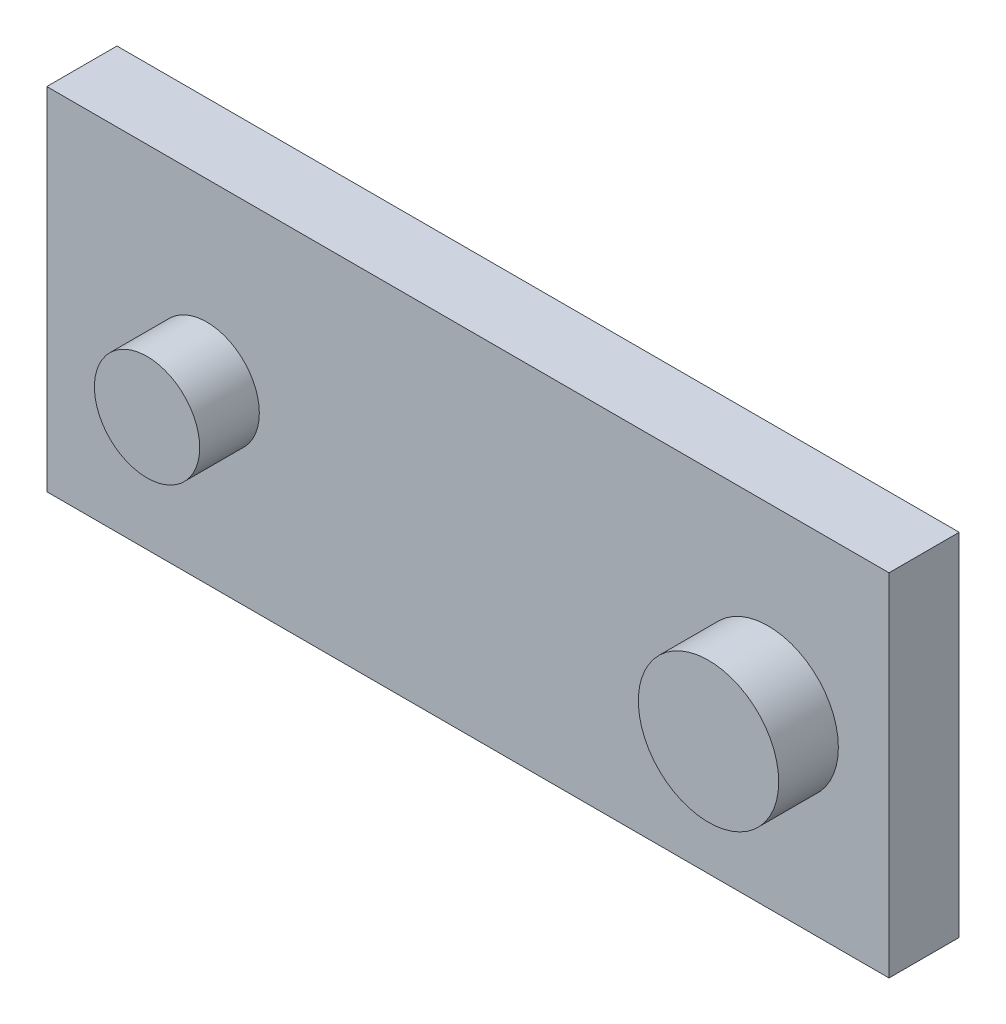
SolidWorks part; units mm, degrees
ref_plane "前视基准面" through (0, 0, 0) normal (0, 0, 1) x (1, 0, 0)
ref_plane "上视基准面" through (0, 0, 0) normal (0, 1, 0) x (1, 0, 0)
ref_plane "右视基准面" through (0, 0, 0) normal (1, 0, 0) x (0, 0, -1)
other "Configuration Table"
sketch "草图1" plane through (0, 0, 0) normal (0, 0, 1) x (1, 0, 0)
  line L1 (-25.9135, 39.1455) -> (94.0865, 39.1455)
  line L2 (-25.9135, 39.1455) -> (-25.9135, -10.8545)
  line L3 (-25.9135, -10.8545) -> (94.0865, -10.8545)
  line L4 (94.0865, 39.1455) -> (94.0865, -10.8545)
  dimension "D4" = 120
  dimension "D5" = 50
extrude "凸台-拉伸1" add sketch "草图1" along normal mid plane 10
sketch "草图2" plane through (0, 0, 5) normal (0, 0, 1) x (1, 0, 0)
  circle A0 centre (-3.1307, 13.9883) radius 7.5
  circle A1 centre (76.8693, 13.9883) radius 10
  dimension "D1" = 15
  dimension "D2" = 20
  dimension "D3" = 80
extrude "凸台-拉伸2" add sketch "草图2" along normal mid plane 17
